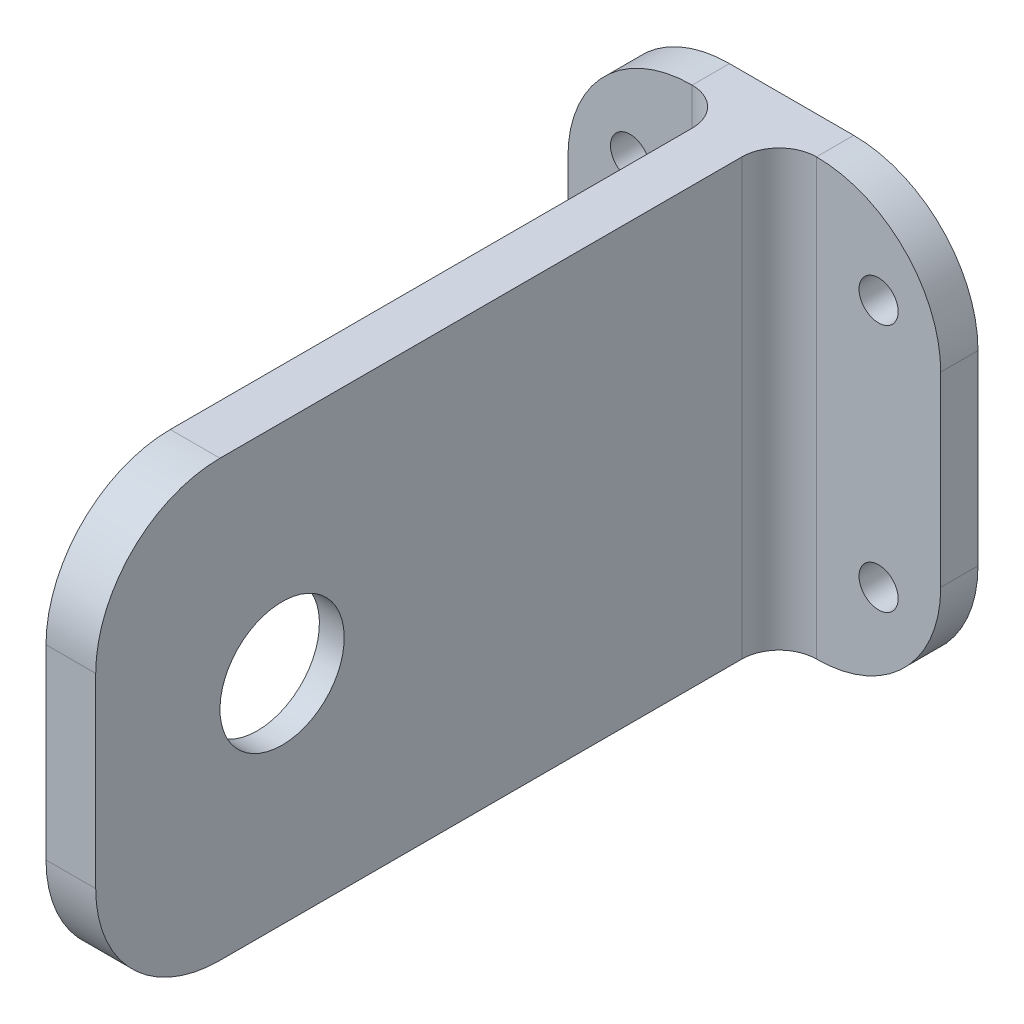
SolidWorks part; units mm, degrees
material "Du"
ref_plane "Front Plane" through (0, 0, 0) normal (0, 0, 1) x (1, 0, 0)
ref_plane "Top Plane" through (0, 0, 0) normal (0, 1, 0) x (1, 0, 0)
ref_plane "Right Plane" through (0, 0, 0) normal (1, 0, 0) x (0, 0, -1)
sketch "Sketch1" plane through (0, 0, 0) normal (0, 0, 1) x (1, 0, 0)
  line L5 (-15, 17.5) -> (15, 17.5)
  line L6 (-15, 17.5) -> (-15, -17.5)
  line L14 (-15, -17.5) -> (15, -17.5)
  line L15 (15, 17.5) -> (15, -17.5)
  line L16 (-15, 17.5) -> (15, -17.5) construction
  line L17 (-15, -17.5) -> (15, 17.5) construction
  point P0 (0, 0)
  dimension "D1" = 30
  dimension "D2" = 35
extrude "Boss-Extrude2" add sketch "Sketch1" along normal blind 3
sketch "Sketch3" plane through (0, 0, 3) normal (0, 0, 1) x (1, 0, 0)
  line L1 (-2, 17.5) -> (2, 17.5)
  line L2 (-2, 17.5) -> (-2, -17.5)
  line L3 (-2, -17.5) -> (2, -17.5)
  line L4 (2, 17.5) -> (2, -17.5)
  line L5 (-2, 17.5) -> (2, -17.5) construction
  line L6 (-2, -17.5) -> (2, 17.5) construction
  point P0 (0, 0)
  dimension "D1" = 4
  dimension "D2" = 35
extrude "Boss-Extrude3" add sketch "Sketch3" along normal blind 55
sketch "Sketch4" plane through (0, 0, 3) normal (0, 0, 1) x (1, 0, 0)
  circle A0 centre (10, 10) radius 1.575
  circle A4 centre (10, -10) radius 1.575
  circle A5 centre (-10, -10) radius 1.575
  circle A6 centre (-10, 10) radius 1.575
  dimension "D1" = 3.15
extrude "Cut-Extrude2" cut sketch "Sketch4" against normal blind 55
fillet "Fillet1" radius 10 6 edges at (0, 17.5, 58) (0, -17.5, 58) (-15, -17.5, 1.5) (15, -17.5, 1.5) (15, 17.5, 1.5) (-15, 17.5, 1.5)
sketch "Sketch5" plane through (-2, 0, 0) normal (-1, 0, 0) x (0, 0, 1)
  line L0 (58, 7.5) -> (58, -7.5) construction
  circle A0 centre (43, 0) radius 11
  dimension "D2" = 22
  dimension "D1" = 15
extrude "Cut-Extrude3" cut sketch "Sketch5" against normal blind 2
sketch "Sketch6" plane through (0, 0, 0) normal (-1, 0, 0) x (0, 0, 1)
  circle A0 centre (43, 0) radius 5
  dimension "D1" = 10
extrude "Cut-Extrude4" cut sketch "Sketch6" against normal blind 2
fillet "Fillet2" radius 3 2 edges at (2, 0, 3) (-2, 0, 3)
